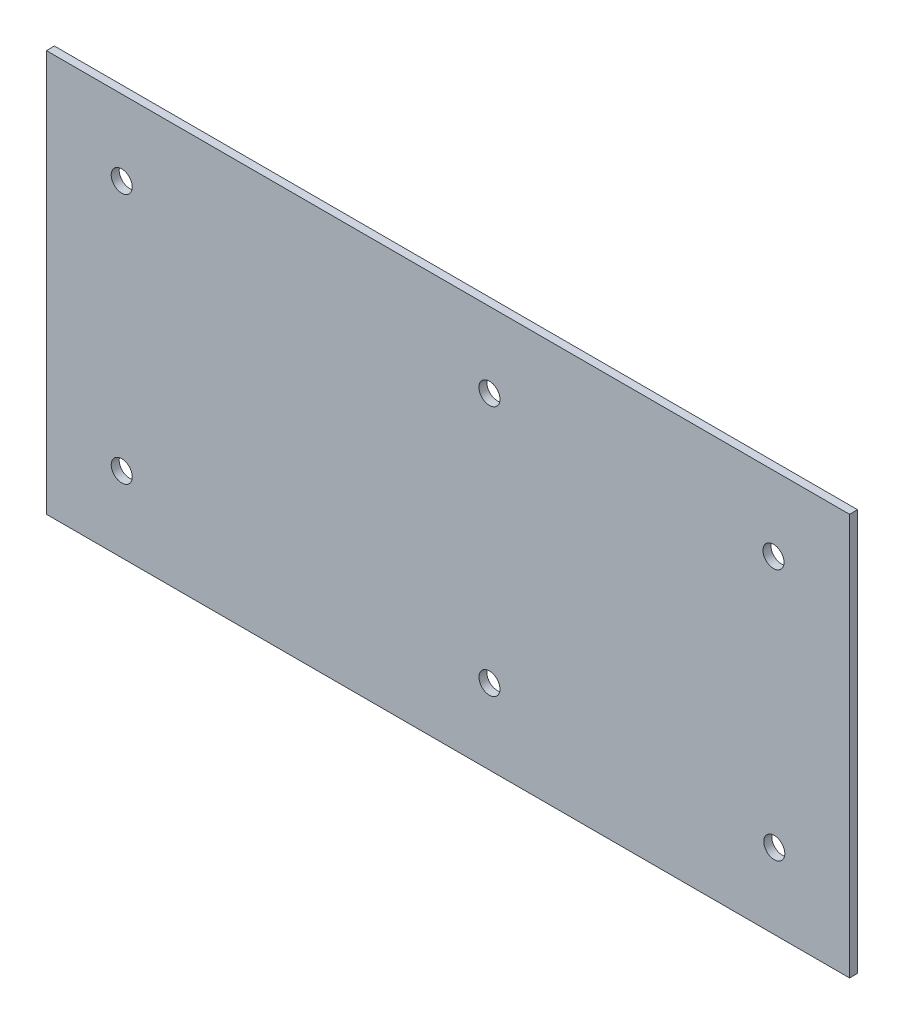
SolidWorks part; units mm, degrees
material "ABS"
ref_plane "X-Y Datum" through (0, 0, 0) normal (0, 0, 1) x (1, 0, 0)
ref_plane "X-Z Datum" through (0, 0, 0) normal (0, 1, 0) x (1, 0, 0)
ref_plane "Y-Z Datum" through (0, 0, 0) normal (1, 0, 0) x (0, 0, -1)
sketch "Sketch1" plane through (0, 0, 0) normal (0, 0, 1) x (1, 0, 0)
  line L0 (-37.7328, 28.0746) -> (102.2672, 28.0746) construction
  line L1 (-37.7328, 28.0746) -> (-37.7328, -31.9254) construction
  line L2 (-37.7328, -31.9254) -> (102.2672, -31.9254) construction
  line L3 (102.2672, 28.0746) -> (102.2672, -31.9254) construction
  line L5 (-47.734, 38.0758) -> (112.2685, 38.0758)
  line L6 (-47.734, 38.0758) -> (-47.734, -41.9267)
  line L7 (-47.734, -41.9267) -> (112.2685, -41.9267)
  line L8 (112.2685, 38.0758) -> (112.2685, -41.9267)
  circle A0 centre (-32.7328, 23.0746) radius 2.0955
  circle A1 centre (-32.7328, -26.9254) radius 2.0955
  circle A2 centre (40.5172, 23.0746) radius 2.0955
  circle A3 centre (97.1085, 23.2333) radius 2.0955
  circle A4 centre (40.5172, -26.9254) radius 2.0955
  circle A5 centre (97.2672, -26.9254) radius 2.0955
  circle A6 centre (-32.7328, 23.0746) radius 15.0012 construction
  circle A7 centre (40.5172, 23.0746) radius 15.0012 construction
  circle A8 centre (97.1085, 23.2333) radius 15.0012 construction
  circle A9 centre (-32.7328, -26.9254) radius 15.0012 construction
  circle A10 centre (40.5172, -26.9254) radius 15.0012 construction
  circle A11 centre (97.2672, -26.9254) radius 15.0012 construction
extrude "Boss-Extrude1" add sketch "Sketch1" along normal blind 1.5875
